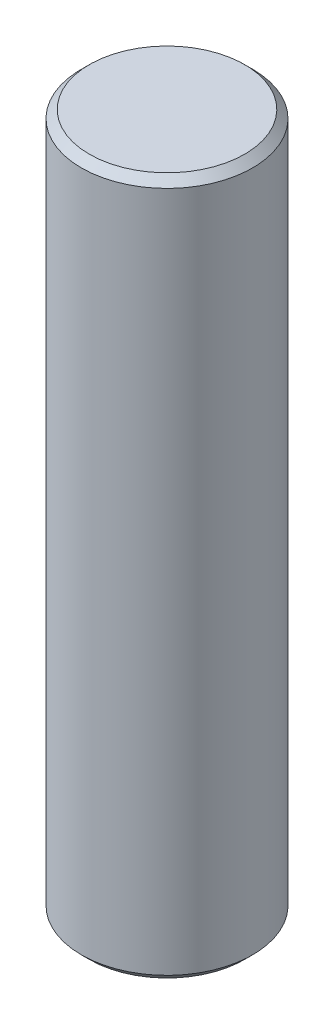
SolidWorks part; units mm, degrees
ref_plane "Front Plane" through (0, 0, 0) normal (0, 0, 1) x (1, 0, 0)
ref_plane "Top Plane" through (0, 0, 0) normal (0, 1, 0) x (1, 0, 0)
ref_plane "Right Plane" through (0, 0, 0) normal (1, 0, 0) x (0, 0, -1)
sketch "Sketch1" plane through (0, 0, 0) normal (0, 1, 0) x (1, 0, 0)
  circle A0 centre (0, 0) radius 2.7
  dimension "D1" = 5.4
extrude "Boss-Extrude1" add sketch "Sketch1" along normal blind 22
chamfer "Chamfer1" distance 0.25 angle 45 2 edges at (0, 0, 2.7) (0, 22, 2.7)
